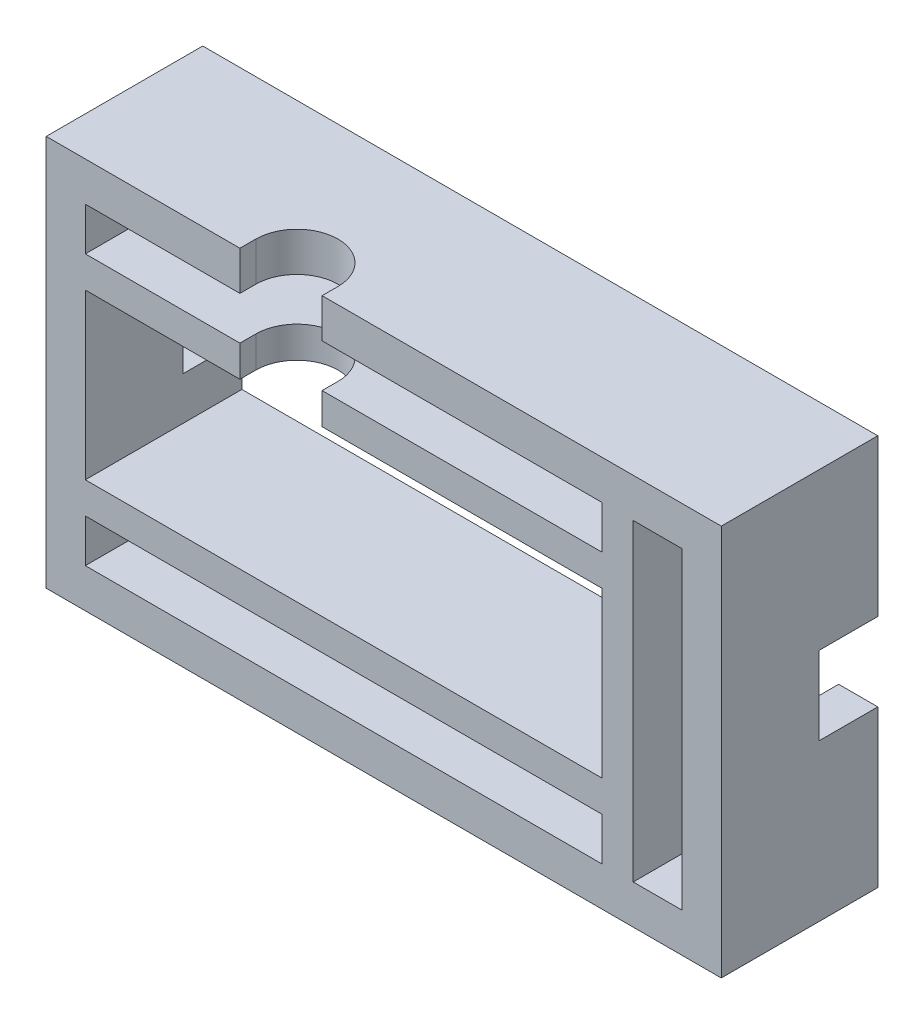
SolidWorks part; units mm, degrees
ref_plane "Ebene vorne" through (0, 0, 0) normal (0, 0, 1) x (1, 0, 0)
ref_plane "Ebene oben" through (0, 0, 0) normal (0, 1, 0) x (1, 0, 0)
ref_plane "Ebene rechts" through (0, 0, 0) normal (1, 0, 0) x (0, 0, -1)
sketch "Sketch1" plane through (0, 0, 0) normal (0, 0, 1) x (1, 0, 0)
  line L1 (-17.25, 10) -> (17.25, 10)
  line L2 (-17.25, 10) -> (-17.25, -10)
  line L3 (-17.25, -10) -> (17.25, -10)
  line L4 (17.25, 10) -> (17.25, -10)
  line L5 (-17.25, 10) -> (17.25, -10) construction
  line L6 (-17.25, -10) -> (17.25, 10) construction
  point P0 (0, 0)
  dimension "D1" = 34.5
  dimension "D2" = 20
extrude "Boss-Extrude1" add sketch "Sketch1" along normal blind 2
sketch "Sketch2" plane through (0, 0, 0) normal (0, 0, 1) x (1, 0, 0)
  line L0 (-15.25, 8) -> (11.15, 8)
  line L1 (-17.25, 10) -> (17.25, 10)
  line L2 (-17.25, 10) -> (-17.25, -10)
  line L3 (-17.25, -10) -> (17.25, -10)
  line L4 (17.25, 10) -> (17.25, 8)
  line L5 (-17.25, 10) -> (17.25, -10) construction
  line L6 (-17.25, -10) -> (17.25, 10) construction
  line L8 (-15.25, -8) -> (11.15, -8)
  line L9 (-15.25, 8) -> (-15.25, 5.8)
  line L12 (17.25, -8) -> (17.25, -10)
  line L13 (15.25, 8) -> (15.25, -8) construction
  line L14 (15.25, 8) -> (15.25, -8)
  line L15 (17.25, 10) -> (17.25, -10) construction
  line L16 (17.25, 8) -> (17.25, -8)
  line L17 (12.75, 8) -> (12.75, -8)
  line L18 (11.15, 8) -> (11.15, 5.8)
  line L19 (-15.25, 5.8) -> (11.15, 5.8)
  line L20 (-15.25, -5.8) -> (11.15, -5.8)
  line L21 (-15.25, -4.2) -> (11.15, -4.2)
  line L22 (-15.25, 4.2) -> (11.15, 4.2)
  line L23 (12.75, 8) -> (15.25, 8)
  line L24 (-15.25, -5.8) -> (-15.25, -8)
  line L25 (-15.25, 8) -> (15.25, 8) construction
  line L26 (11.15, -5.8) -> (11.15, -8)
  line L27 (-15.25, 8) -> (-15.25, -8) construction
  line L28 (12.75, -8) -> (15.25, -8)
  line L29 (11.15, 4.2) -> (11.15, -4.2)
  line L30 (-15.25, -8) -> (15.25, -8) construction
  line L31 (-15.25, 4.2) -> (-15.25, -4.2)
  point P0 (0, 0)
  dimension "D2" = 1.6
  dimension "D3" = 2.5
  dimension "D4" = 2.2
  dimension "D5" = 1.6
  dimension "D6" = 2.2
  dimension "D7" = 1.6
  dimension "D8" = 8.4
  dimension "D1" = 2
extrude "Boss-Extrude2" add sketch "Sketch2" along normal blind 10
sketch "Sketch3" plane through (0, 0, 0) normal (1, 0, 0) x (0, 0, -1)
  line L0 (-2, 2) -> (-2, -2)
  line L1 (-5, 2) -> (-2, 2)
  line L2 (-5, 2) -> (-5, -2)
  line L3 (-5, -2) -> (-2, -2)
  point P0 (0, 0)
  point P1 (-2, 0)
  dimension "D1" = 4
  dimension "D2" = 2
  dimension "D3" = 3
extrude "Cut-Extrude1" cut sketch "Sketch3" against normal blind 17.5 and the other way blind 17.5
sketch "Sketch4" plane through (0, 10, 0) normal (0, 1, 0) x (1, 0, 0)
  line L0 (-17.25, -10) -> (-17.25, -12) construction
  line L1 (-17.25, -12) -> (-5.25, -12) construction
  line L2 (-5.25, 0) -> (-5.25, -9.1875) construction
  line L3 (-17.25, -10) -> (-17.25, 0) construction
  line L6 (-7.35, -9.1875) -> (-7.35, -11.2875)
  line L7 (-7.35, -11.2875) -> (-3.15, -11.2875)
  line L8 (-3.15, -9.1875) -> (-3.15, -11.2875)
  arc A0 (-3.15, -9.1875) -> (-7.35, -9.1875) centre (-5.25, -9.1875) ccw
  dimension "D2" = 4.2
  dimension "D1" = 9.1875
  dimension "D3" = 12
  dimension "D4" = 12
  dimension "D5" = 2
  dimension "D6" = 2.8125
extrude "Cut-Extrude2" cut sketch "Sketch4" against normal blind 10
fillet "Fillet1" radius 2 2 edges at (0, 10, 0) (0, -10, 0)
sketch "Sketch6" plane through (0, 10, 0) normal (0, 1, 0) x (1, 0, 0)
  line L0 (-7.75, -2) -> (-2.75, -2)
  line L1 (17.25, -2) -> (-17.25, -2) construction
  line L2 (-2.75, -2) -> (-2.75, -4)
  line L3 (-2.75, -4) -> (-4.5, -4)
  line L4 (-7.75, -4) -> (-7.75, -2)
  line L5 (-5.25, -5) -> (-5.25, -7.0875) construction
  line L6 (-6, -4) -> (-7.75, -4)
  line L8 (-6, -4) -> (-6, -6)
  line L9 (-6, -6) -> (-4.5, -6)
  line L10 (-4.5, -4) -> (-4.5, -6)
  line L11 (-17.25, -10) -> (-17.25, -2) construction
  arc A0 (-3.15, -9.1875) -> (-7.35, -9.1875) centre (-5.25, -9.1875) ccw construction
  dimension "D1" = 5
  dimension "D2" = 2
  dimension "D3" = 1.5
  dimension "D4" = 0.75
  dimension "D5" = 2
  dimension "D6" = 1.0875
extrude "Boss-Extrude3" add sketch "Sketch6" against normal blind 5
sketch "Sketch7" plane through (0, 0, 0) normal (0, 0, 1) x (1, 0, 0)
  line L1 (-17.25, -10) -> (17.25, -10)
  line L2 (-17.25, -10) -> (-17.25, 10)
  line L3 (-17.25, 10) -> (17.25, 10)
  line L4 (17.25, -10) -> (17.25, 10)
  line L5 (-17.25, -10) -> (17.25, 10) construction
  line L6 (-17.25, 10) -> (17.25, -10) construction
  point P0 (0, 0)
extrude "Cut-Extrude3" cut sketch "Sketch7" along normal blind 2
